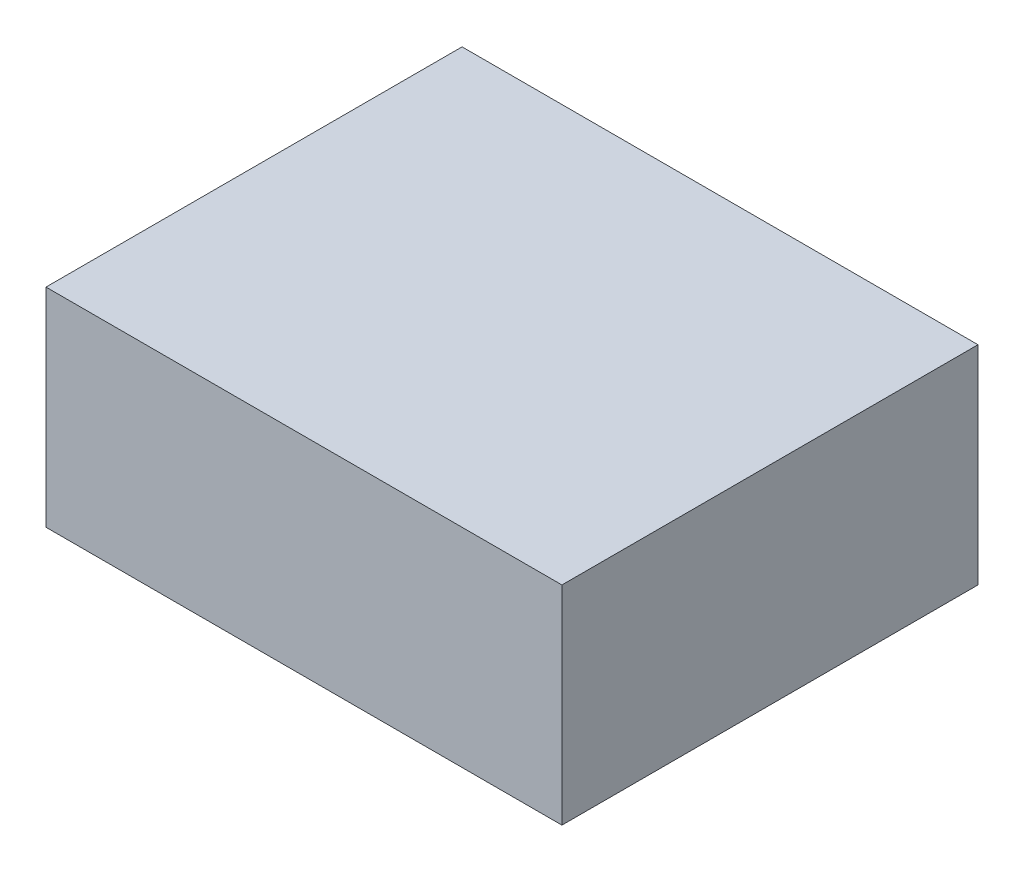
SolidWorks part; units mm, degrees
ref_plane "前视基准面" through (0, 0, 0) normal (0, 0, 1) x (1, 0, 0)
ref_plane "上视基准面" through (0, 0, 0) normal (0, 1, 0) x (1, 0, 0)
ref_plane "右视基准面" through (0, 0, 0) normal (1, 0, 0) x (0, 0, -1)
other "Configuration Table"
sketch "草图1" plane through (0, 0, 0) normal (0, 0, 1) x (1, 0, 0)
  line L1 (-6.2, 2.5) -> (6.2, 2.5)
  line L2 (-6.2, 2.5) -> (-6.2, -2.5)
  line L3 (-6.2, -2.5) -> (6.2, -2.5)
  line L4 (6.2, 2.5) -> (6.2, -2.5)
  line L5 (-6.2, 2.5) -> (6.2, -2.5) construction
  line L6 (-6.2, -2.5) -> (6.2, 2.5) construction
  point P0 (0, 0)
  dimension "D1" = 12.4
  dimension "D2" = 5
extrude "凸台-拉伸1" add sketch "草图1" along normal blind 10
